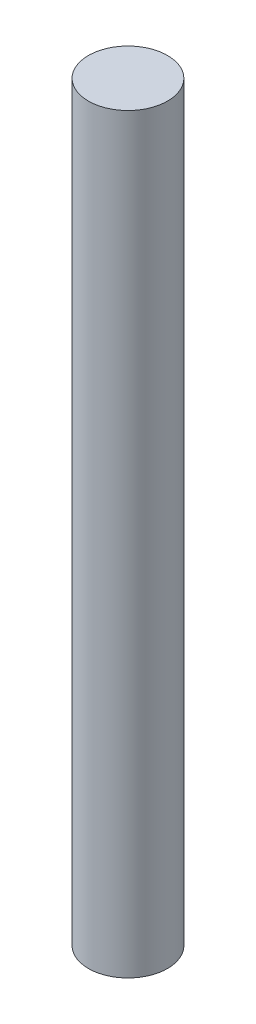
SolidWorks part; units mm, degrees
ref_plane "Front Plane" through (0, 0, 0) normal (0, 0, 1) x (1, 0, 0)
ref_plane "Top Plane" through (0, 0, 0) normal (0, 1, 0) x (1, 0, 0)
ref_plane "Right Plane" through (0, 0, 0) normal (1, 0, 0) x (0, 0, -1)
sketch "Sketch1" plane through (0, 0, 0) normal (0, 1, 0) x (1, 0, 0)
  circle A0 centre (0, 0) radius 0.254
  dimension "D1" = 0.508
extrude "Boss-Extrude1" add sketch "Sketch1" against normal blind 4.826
